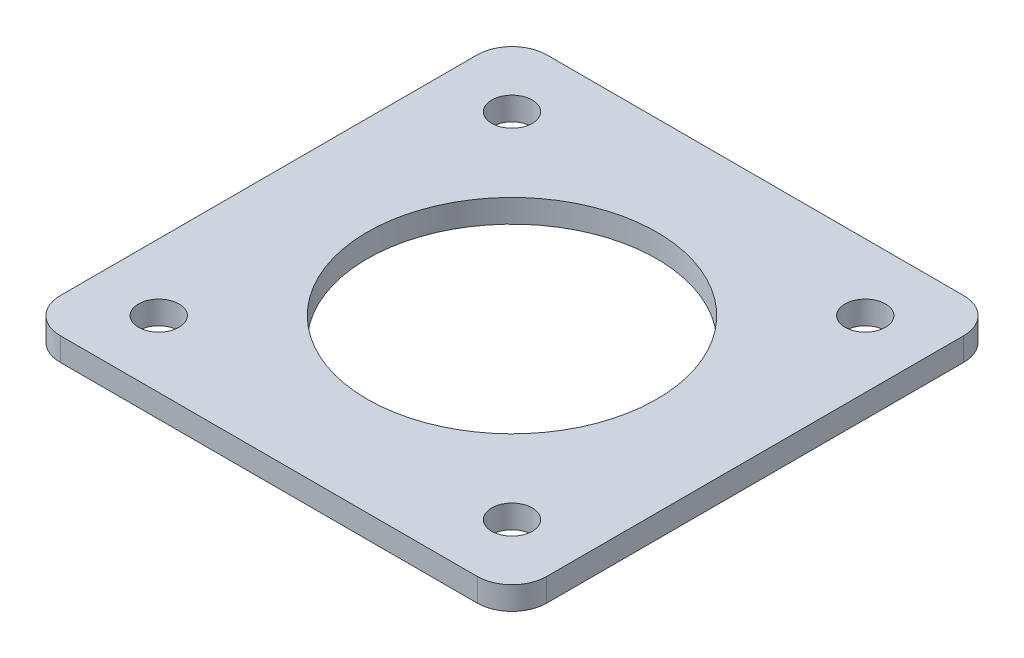
SolidWorks part; units mm, degrees
ref_plane "Płaszczyzna przednia" through (0, 0, 0) normal (0, 0, 1) x (1, 0, 0)
ref_plane "Płaszczyzna górna" through (0, 0, 0) normal (0, 1, 0) x (1, 0, 0)
ref_plane "Płaszczyzna prawa" through (0, 0, 0) normal (1, 0, 0) x (0, 0, -1)
sketch "Szkic1" plane through (0, 0, 0) normal (0, 1, 0) x (1, 0, 0)
  line L0 (21, 42) -> (21, 0) construction
  line L1 (3, 0) -> (39, 0)
  line L2 (0, 3) -> (0, 39)
  line L3 (3, 42) -> (39, 42)
  line L4 (42, 3) -> (42, 39)
  line L5 (0, 21) -> (42, 21) construction
  circle A0 centre (21, 21) radius 12.5
  circle A1 centre (5.75, 36.25) radius 1.75
  circle A2 centre (36.25, 36.25) radius 1.75
  circle A3 centre (36.25, 5.75) radius 1.75
  circle A4 centre (5.75, 5.75) radius 1.75
  arc A5 (3, 0) -> (0, 3) centre (3, 3) cw
  arc A6 (39, 0) -> (42, 3) centre (39, 3) ccw
  arc A7 (39, 42) -> (42, 39) centre (39, 39) cw
  arc A8 (0, 39) -> (3, 42) centre (3, 39) cw
  point P21 (0, 0)
  point P24 (42, 0)
  point P27 (42, 42)
  point P30 (0, 42)
  dimension "D3" = 25
  dimension "D4" = 3.5
  dimension "D5" = 5.75
  dimension "D6" = 5.75
  dimension "D7" = 3
  dimension "D1" = 42
  dimension "D2" = 42
extrude "Dodanie-wyciągnięcie1" add sketch "Szkic1" along normal blind 2
